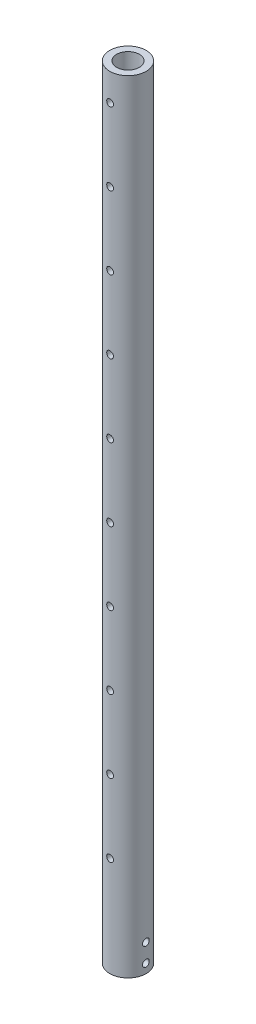
SolidWorks part; units mm, degrees
material "7075-O (SS)"
ref_plane "Front Plane" through (0, 0, 0) normal (0, 0, 1) x (1, 0, 0)
ref_plane "Top Plane" through (0, 0, 0) normal (0, 1, 0) x (1, 0, 0)
ref_plane "Right Plane" through (0, 0, 0) normal (1, 0, 0) x (0, 0, -1)
sketch "Sketch1" plane through (0, 0, 0) normal (0, 1, 0) x (1, 0, 0)
  line L0 (-143.9942, 0) -> (160.8058, 0) construction
  line L1 (0, 109.6403) -> (0, -97.9453) construction
  circle A0 centre (0, 0) radius 25.4
  circle A2 centre (0, 0) radius 15.875
  point P11 (0, 0)
  dimension "D1" = 50.8
  dimension "D2" = 31.75
extrude "Boss-Extrude1" add sketch "Sketch1" along normal blind 1092.2
sketch "Sketch2" plane through (0, 0, 0) normal (0, 0, 1) x (1, 0, 0)
  circle A0 centre (0, 38.1) radius 4.7625
  dimension "D2" = 9.525
  dimension "D1" = 38.1
sketch "Sketch5" plane through (0, 0, 0) normal (0, -1, 0) x (1, 0, 0)
  text T0 "B"
extrude "Cut-Extrude3" cut sketch "Sketch5" against normal blind 5.08
sketch "Sketch6" [suppressed] plane through (0, 1117.6, 0) normal (0, 1, 0) x (1, 0, 0)
  line L1 (-53.975, 53.975) -> (53.975, 53.975)
  line L2 (-53.975, 53.975) -> (-53.975, -53.975)
  line L3 (-53.975, -53.975) -> (53.975, -53.975)
  line L4 (53.975, 53.975) -> (53.975, -53.975)
  line L5 (-53.975, 53.975) -> (53.975, -53.975) construction
  line L6 (-53.975, -53.975) -> (53.975, 53.975) construction
  point P0 (0, 0)
  dimension "D1" = 107.95
  dimension "D2" = 107.95
extrude "Boss-Extrude2" [suppressed] add sketch "Sketch6" along normal blind 6.35
sketch "Sketch7" [suppressed] plane through (0, 1123.95, 0) normal (0, 1, 0) x (1, 0, 0)
  line L0 (-53.975, 53.975) -> (-53.975, -53.975) construction
  line L1 (53.975, 53.975) -> (-53.975, 53.975) construction
  line L2 (-53.975, 0) -> (53.975, 0) construction
  line L3 (53.975, -53.975) -> (53.975, 53.975) construction
  line L4 (0, 53.975) -> (0, -53.975) construction
  line L5 (-53.975, -53.975) -> (53.975, -53.975) construction
  circle A0 centre (-28.575, 28.575) radius 4.7625
  circle A1 centre (-28.575, -28.575) radius 4.7625
  circle A2 centre (28.575, -28.575) radius 4.7625
  circle A3 centre (28.575, 28.575) radius 4.7625
  dimension "D1" = 25.4
  dimension "D2" = 25.4
  dimension "D3" = 9.525
extrude "Cut-Extrude4" [suppressed] cut sketch "Sketch7" against normal through all
sketch "Sketch8" [suppressed] plane through (0, 1123.95, 0) normal (0, 1, 0) x (1, 0, 0)
  text T0 "TOP"
extrude "Cut-Extrude6" [suppressed] cut sketch "Sketch8" against normal blind 2.54
sketch "Sketch9" plane through (0, 0, 0) normal (1, 0, 0) x (0, 0, -1)
  line L0 (-150.2486, 926.24) -> (124.2388, 926.24) construction
sketch "Sketch10" plane through (0, 0, -50.8) normal (0, 0, -1) x (-1, 0, 0)
  circle A0 centre (0, 12.7296) radius 4.7625
sketch "Sketch11" plane through (0, 0, 0) normal (1, 0, 0) x (0, 0, -1)
  circle A0 centre (0, 38.1) radius 4.7625
  dimension "D2" = 9.525
  dimension "D1" = 38.1
extrude "Cut-Extrude8" cut sketch "Sketch11" against normal mid plane 71.628
sketch "Sketch12" plane through (0, 0, 0) normal (1, 0, 0) x (0, 0, -1)
  circle A0 centre (0, 12.7) radius 4.7625
  dimension "D1" = 9.525
  dimension "D2" = 12.7
extrude "Cut-Extrude9" cut sketch "Sketch12" against normal mid plane 71.628
sketch "Sketch16" plane through (0, 0, 0) normal (0, 0, 1) x (1, 0, 0)
  circle A0 centre (0, 139.7) radius 4.7625
  circle A1 centre (0, 241.3) radius 4.7625
  circle A2 centre (0, 342.9) radius 4.7625
  circle A3 centre (0, 444.5) radius 4.7625
  circle A4 centre (0, 546.1) radius 4.7625
  circle A5 centre (0, 647.7) radius 4.7625
  circle A6 centre (0, 749.3) radius 4.7625
  circle A7 centre (0, 850.9) radius 4.7625
  circle A8 centre (0, 952.5) radius 4.7625
  circle A9 centre (0, 1054.1) radius 4.7625
  dimension "D1" = 9.525
  dimension "D2" = 139.7
  dimension "D3" = 10
extrude "Cut-Extrude10" cut sketch "Sketch16" against normal mid plane 127
